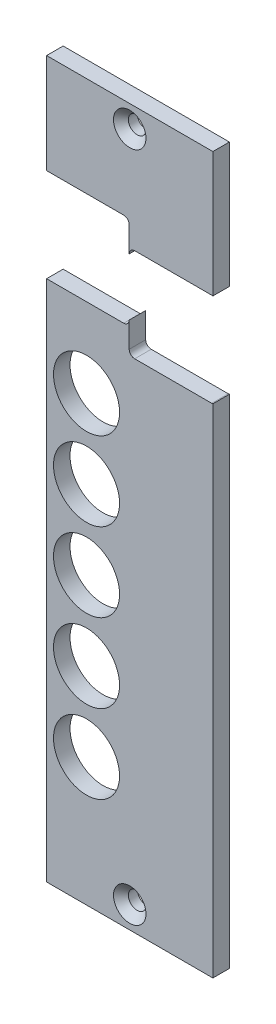
SolidWorks part; units mm, degrees
ref_plane "Ebene vorne" through (0, 0, 0) normal (0, 0, 1) x (1, 0, 0)
ref_plane "Ebene oben" through (0, 0, 0) normal (0, 1, 0) x (1, 0, 0)
ref_plane "Ebene rechts" through (0, 0, 0) normal (1, 0, 0) x (0, 0, -1)
sketch "Model" plane through (0, 0, 0) normal (0, 0, 1) x (1, 0, 0)
  line L0 (30.2, 130) -> (30.2, 0)
  line L1 (30.2, 0) -> (0, 0)
  line L2 (0, 0) -> (0, 130)
  line L3 (0, 130) -> (30.2, 130)
  line L4 (20.0925, 38.872) -> (19.1527, 38.872)
  line L5 (19.1527, 38.872) -> (19.1527, 36.309)
  line L6 (19.1527, 36.309) -> (20.2349, 36.309)
  line L7 (20.2349, 37.5905) -> (19.1527, 37.5905)
  line L8 (10.0887, 122.263) -> (10.9715, 122.263)
  line L9 (11.7974, 121.4087) -> (11.7974, 120.5543)
  line L10 (10.9715, 119.7) -> (10.0887, 119.7)
  line L11 (10.0887, 119.7) -> (10.0887, 122.263)
  line L12 (12.4817, 122.262) -> (12.4817, 122.1196)
  line L13 (12.4817, 121.4077) -> (12.4817, 119.699)
  line L14 (14.5896, 121.4077) -> (14.5896, 120.4109)
  line L15 (13.1657, 120.354) -> (13.1657, 120.6957)
  line L16 (14.5896, 120.6957) -> (14.5896, 119.5566)
  line L17 (15.2737, 122.262) -> (15.2737, 122.1196)
  line L18 (15.2737, 121.4077) -> (15.2737, 119.699)
  line L19 (16.213, 122.262) -> (16.213, 121.4077)
  line L20 (16.213, 121.4077) -> (16.6402, 121.4077)
  line L21 (16.6402, 121.4077) -> (15.9283, 121.4077)
  line L22 (15.9283, 121.4077) -> (16.213, 121.4077)
  line L23 (16.213, 121.4077) -> (16.213, 120.0407)
  line L24 (18.8036, 121.4067) -> (18.8036, 120.4099)
  line L25 (17.3227, 120.4099) -> (17.3227, 120.6947)
  line L26 (18.8036, 120.6947) -> (18.8036, 120.0113)
  line L27 (19.8287, 122.261) -> (19.8287, 120.0397)
  line L28 (5.3478, 115.9015) -> (5.9743, 115.9015)
  line L29 (5.9743, 115.9015) -> (5.9743, 115.4743)
  line L30 (4.1517, 115.4743) -> (4.1517, 116.3287)
  line L31 (8.1396, 116.3287) -> (8.1396, 115.3319)
  line L32 (6.6587, 115.3319) -> (6.6587, 115.6167)
  line L33 (8.1396, 115.6167) -> (8.1396, 114.9333)
  line L34 (9.1657, 114.621) -> (9.1657, 117.184)
  line L35 (9.1657, 117.184) -> (10.8744, 114.621)
  line L36 (10.8744, 114.621) -> (10.8744, 117.184)
  line L37 (13.3817, 117.184) -> (13.3817, 114.621)
  line L38 (14.0657, 114.621) -> (14.0657, 116.3297)
  line L39 (14.0657, 116.3297) -> (14.0657, 115.6177)
  line L40 (15.4896, 115.6177) -> (15.4896, 114.621)
  line L41 (16.1727, 116.3297) -> (16.8847, 114.621)
  line L42 (16.8847, 114.621) -> (17.5966, 116.3297)
  line L43 (18.2797, 115.4753) -> (19.7036, 115.4753)
  line L44 (19.7036, 115.4753) -> (19.7036, 115.6177)
  line L45 (18.2797, 115.6177) -> (18.2797, 115.3329)
  line L46 (20.3867, 114.621) -> (20.3867, 116.3297)
  line L47 (20.3867, 116.3297) -> (20.3867, 115.7601)
  line L48 (22.066, 117.184) -> (22.066, 116.3297)
  line L49 (22.066, 116.3297) -> (22.4932, 116.3297)
  line L50 (22.4932, 116.3297) -> (21.7813, 116.3297)
  line L51 (21.7813, 116.3297) -> (22.066, 116.3297)
  line L52 (22.066, 116.3297) -> (22.066, 114.9627)
  line L53 (23.1757, 115.4753) -> (24.5996, 115.4753)
  line L54 (24.5996, 115.4753) -> (24.5996, 115.6177)
  line L55 (23.1757, 115.6177) -> (23.1757, 115.3329)
  line L56 (25.2827, 114.621) -> (25.2827, 116.3297)
  line L57 (25.2827, 116.3297) -> (25.2827, 115.7601)
  line L58 (19.2885, 51.3209) -> (20.7124, 51.3209)
  line L59 (19.0037, 50.609) -> (20.0005, 53.172)
  line L60 (20.0005, 53.172) -> (20.9972, 50.609)
  line L61 (3.101, 88.25) -> (27.099, 88.25)
  line L62 (3.101, 113.5) -> (27.099, 113.5)
  line L63 (19.1757, 22.7746) -> (19.1757, 21.8064)
  line L64 (15.8007, 81.772) -> (16.6835, 81.772)
  line L65 (17.5094, 80.9177) -> (17.5094, 80.0633)
  line L66 (16.6835, 79.209) -> (15.8007, 79.209)
  line L67 (15.8007, 79.209) -> (15.8007, 81.772)
  line L68 (18.1937, 80.9746) -> (18.1937, 80.0064)
  line L69 (22.7209, 80.4905) -> (24.2018, 80.4905)
  line L70 (23.4614, 79.7501) -> (23.4614, 81.2309)
  line L71 (15.9857, 67.472) -> (16.8685, 67.472)
  line L72 (17.6944, 66.6177) -> (17.6944, 65.7633)
  line L73 (16.8685, 64.909) -> (15.9857, 64.909)
  line L74 (15.9857, 64.909) -> (15.9857, 67.472)
  line L75 (18.3787, 66.6746) -> (18.3787, 65.7064)
  line L76 (22.5357, 66.1905) -> (24.0166, 66.1905)
  line L77 (13.7528, 72.994) -> (13.7528, 72.8859)
  line L78 (12.6285, 72.8859) -> (12.6285, 73.7292)
  line L79 (14.2725, 73.7941) -> (14.2725, 72.8859)
  line L80 (15.3968, 72.8859) -> (15.3968, 73.7941)
  line L81 (15.9165, 73.7941) -> (15.9165, 72.8859)
  line L82 (17.0408, 72.8859) -> (17.0408, 73.7941)
  line L83 (18.9445, 74.313) -> (19.5931, 72.367)
  line L84 (19.5931, 72.367) -> (20.2418, 74.313)
  line L85 (22.1435, 72.367) -> (22.1435, 73.6643)
  line L86 (22.1435, 73.6643) -> (22.1435, 73.2319)
  line L87 (23.0084, 73.2319) -> (23.0084, 72.367)
  line L88 (23.0084, 72.367) -> (23.0084, 73.2319)
  line L89 (23.8732, 73.2319) -> (23.8732, 72.367)
  line L90 (25.5158, 73.6653) -> (25.5158, 72.9086)
  line L91 (24.3915, 72.9086) -> (24.3915, 73.1248)
  line L92 (25.5158, 73.1248) -> (25.5158, 72.6058)
  line L93 (26.2935, 73.6653) -> (27.3746, 72.368)
  line L94 (26.2935, 72.368) -> (27.3746, 73.6653)
  line L95 (0, 94.9) -> (14, 94.9)
  line L96 (15, 95.9) -> (15, 110.9)
  line L97 (14, 111.9) -> (0, 111.9)
  line L98 (-1, 110.9) -> (-1, 95.9)
  line L99 (16, 90.3) -> (30, 90.3)
  line L100 (31, 91.3) -> (31, 106.3)
  line L101 (30, 107.3) -> (16, 107.3)
  line L102 (15, 106.3) -> (15, 91.3)
  arc A0 (20.0925, 37.5905) -> (20.0925, 38.872) centre (20.0925, 38.2313) ccw
  arc A1 (20.2349, 36.309) -> (20.2349, 37.5905) centre (20.2349, 36.9498) ccw
  arc A2 (11.7974, 121.4087) -> (10.9715, 122.263) centre (10.9384, 121.4046) ccw
  arc A3 (10.9715, 119.7) -> (11.7974, 120.5543) centre (10.973, 120.5249) ccw
  arc A4 (13.1657, 120.354) -> (14.5896, 120.4109) centre (13.8777, 120.3825) ccw
  arc A5 (14.5896, 120.6957) -> (13.1657, 120.6957) centre (13.8777, 120.6957) ccw
  arc A6 (13.3651, 119.044) -> (14.5896, 119.5566) centre (13.8717, 119.5528) ccw
  arc A7 (16.213, 120.0407) -> (16.4978, 119.699) centre (16.5603, 120.0406) ccw
  arc A8 (17.3227, 120.4099) -> (18.8036, 120.4099) centre (18.0632, 120.4099) ccw
  arc A9 (18.8036, 120.6947) -> (17.3227, 120.6947) centre (18.0632, 120.6947) ccw
  arc A10 (18.8036, 120.0113) -> (19.1453, 119.641) centre (19.2165, 120.0495) ccw
  arc A11 (19.8287, 120.0397) -> (20.1135, 119.698) centre (20.176, 120.0396) ccw
  arc A12 (4.1517, 115.4743) -> (5.9743, 115.4743) centre (5.063, 115.4743) ccw
  arc A13 (5.775, 116.8128) -> (4.1517, 116.3287) centre (5.0294, 116.3494) ccw
  arc A14 (6.6587, 115.3319) -> (8.1396, 115.3319) centre (7.3992, 115.3319) ccw
  arc A15 (8.1396, 115.6167) -> (6.6587, 115.6167) centre (7.3992, 115.6167) ccw
  arc A16 (8.1396, 114.9333) -> (8.4813, 114.563) centre (8.5525, 114.9715) ccw
  arc A17 (15.4896, 115.6177) -> (14.0657, 115.6177) centre (14.7777, 115.6177) ccw
  arc A18 (19.7036, 115.6177) -> (18.2797, 115.6177) centre (18.9917, 115.6177) ccw
  arc A19 (18.2797, 115.3329) -> (19.6182, 114.8773) centre (19.0263, 115.3323) ccw
  arc A20 (20.5291, 116.1588) -> (20.3867, 115.7601) centre (21.016, 115.7601) ccw
  arc A21 (21.1556, 116.1588) -> (20.5291, 116.1588) centre (20.8424, 115.9013) ccw
  arc A22 (22.066, 114.9627) -> (22.3508, 114.621) centre (22.4133, 114.9626) ccw
  arc A23 (24.5996, 115.6177) -> (23.1757, 115.6177) centre (23.8877, 115.6177) ccw
  arc A24 (23.1757, 115.3329) -> (24.5142, 114.8773) centre (23.9223, 115.3323) ccw
  arc A25 (25.4251, 116.1588) -> (25.2827, 115.7601) centre (25.912, 115.7601) ccw
  arc A26 (26.0516, 116.1588) -> (25.4251, 116.1588) centre (25.7384, 115.9013) ccw
  arc A27 (20.742, 23.2018) -> (19.1757, 22.7746) centre (20.0104, 22.7992) ccw
  arc A28 (19.1757, 21.8064) -> (20.8274, 21.4931) centre (20.0316, 21.8078) ccw
  arc A29 (17.5094, 80.9177) -> (16.6835, 81.772) centre (16.6504, 80.9136) ccw
  arc A30 (16.6835, 79.209) -> (17.5094, 80.0633) centre (16.685, 80.0339) ccw
  arc A31 (19.76, 81.4018) -> (18.1937, 80.9746) centre (19.0284, 80.9992) ccw
  arc A32 (18.1937, 80.0064) -> (19.8454, 79.6931) centre (19.0496, 80.0078) ccw
  arc A33 (17.6944, 66.6177) -> (16.8685, 67.472) centre (16.8354, 66.6136) ccw
  arc A34 (16.8685, 64.909) -> (17.6944, 65.7633) centre (16.87, 65.7339) ccw
  arc A35 (19.945, 67.1018) -> (18.3787, 66.6746) centre (19.2134, 66.6992) ccw
  arc A36 (18.3787, 65.7064) -> (20.0304, 65.3931) centre (19.2346, 65.7078) ccw
  arc A37 (13.7528, 72.994) -> (12.6285, 72.994) centre (13.1906, 72.994) ccw
  arc A38 (12.6285, 72.8859) -> (13.7528, 72.8859) centre (13.1906, 72.8859) ccw
  arc A39 (13.6447, 74.1833) -> (12.6285, 73.7292) centre (13.2274, 73.7531) ccw
  arc A40 (14.2725, 72.8859) -> (15.3968, 72.8859) centre (14.8346, 72.8859) ccw
  arc A41 (15.3968, 73.7941) -> (14.2725, 73.7941) centre (14.8346, 73.7941) ccw
  arc A42 (15.9165, 72.8859) -> (17.0408, 72.8859) centre (16.4786, 72.8859) ccw
  arc A43 (17.0408, 73.7941) -> (15.9165, 73.7941) centre (16.4786, 73.7941) ccw
  arc A44 (23.0084, 73.2319) -> (22.1435, 73.2319) centre (22.5759, 73.2319) ccw
  arc A45 (23.8732, 73.2319) -> (23.0084, 73.2319) centre (23.4408, 73.2319) ccw
  arc A46 (24.3915, 72.9086) -> (25.5158, 72.9086) centre (24.9536, 72.9086) ccw
  arc A47 (25.5158, 73.1248) -> (24.3915, 73.1248) centre (24.9536, 73.1248) ccw
  arc A48 (25.5158, 72.6058) -> (25.7753, 72.3248) centre (25.8293, 72.6349) ccw
  circle A49 centre (15.1, 4) radius 3
  circle A50 centre (15.1, 4) radius 1.6
  circle A51 centre (15.1, 4) radius 3
  circle A52 centre (15.1, 4) radius 1.6
  circle A53 centre (15.1, 126) radius 3
  circle A54 centre (15.1, 126) radius 1.6
  circle A55 centre (15.1, 126) radius 3
  circle A56 centre (15.1, 126) radius 1.6
  arc A57 (-1, 95.9) -> (0, 94.9) centre (0, 95.9) ccw
  arc A58 (14, 94.9) -> (15, 95.9) centre (14, 95.9) ccw
  arc A59 (15, 110.9) -> (14, 111.9) centre (14, 110.9) ccw
  arc A60 (0, 111.9) -> (-1, 110.9) centre (0, 110.9) ccw
  arc A61 (15, 91.3) -> (16, 90.3) centre (16, 91.3) ccw
  arc A62 (30, 90.3) -> (31, 91.3) centre (30, 91.3) ccw
  arc A63 (31, 106.3) -> (30, 107.3) centre (30, 106.3) ccw
  arc A64 (16, 107.3) -> (15, 106.3) centre (16, 106.3) ccw
  circle A65 centre (7.25, 23.29) radius 6
  circle A66 centre (7.25, 37.59) radius 6
  circle A67 centre (7.25, 51.89) radius 6
  circle A68 centre (7.25, 66.19) radius 6
  circle A69 centre (7.25, 80.49) radius 6
extrude "Aufsatz-Linear austragen1" add sketch "Model" against normal blind 3
chamfer "Fase1" distance 1.35 angle 45 1 edges at (16.7, 4, 0)
chamfer "Fase2" distance 1.35 angle 45 1 edges at (16.7, 126, 0)
